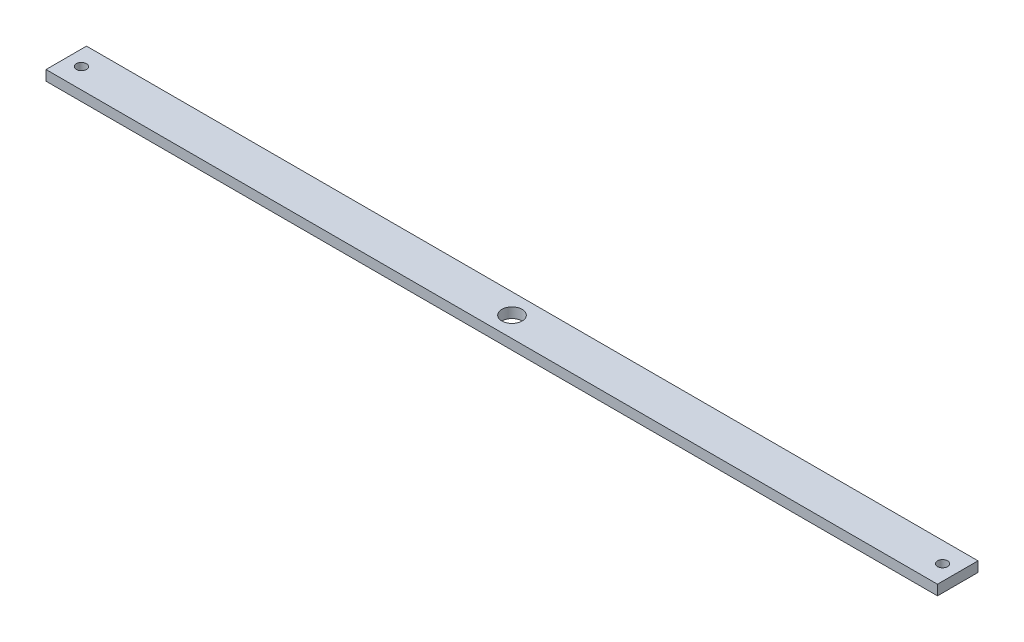
SolidWorks part; units mm, degrees
ref_plane "Front Plane" through (0, 0, 0) normal (0, 0, 1) x (1, 0, 0)
ref_plane "Top Plane" through (0, 0, 0) normal (0, 1, 0) x (1, 0, 0)
ref_plane "Right Plane" through (0, 0, 0) normal (1, 0, 0) x (0, 0, -1)
sketch "Sketch1" plane through (0, 0, 0) normal (0, 1, 0) x (1, 0, 0)
  line L1 (-279.4, -12.7) -> (279.4, -12.7)
  line L2 (-279.4, -12.7) -> (-279.4, 12.7)
  line L3 (-279.4, 12.7) -> (279.4, 12.7)
  line L4 (279.4, -12.7) -> (279.4, 12.7)
  line L5 (-279.4, -12.7) -> (279.4, 12.7) construction
  line L6 (-279.4, 12.7) -> (279.4, -12.7) construction
  point P0 (0, 0)
  dimension "D1" = 558.8
  dimension "D2" = 25.4
extrude "Boss-Extrude1" add sketch "Sketch1" along normal blind 6.35
hole_wizard "1/4 (0.25) Diameter Hole1" positions "Sketch3" profile "Sketch4" hole size "1/4" standard "ANSI Inch"
sketch "Sketch3" plane through (0, 6.35, 0) normal (0, 1, 0) x (1, 0, 0)
  line L0 (-279.4, 0) -> (-269.875, 0) construction
  line L1 (-279.4, 12.7) -> (-279.4, -12.7) construction
  line L4 (279.4, 0) -> (269.875, 0) construction
  line L5 (279.4, -12.7) -> (279.4, 12.7) construction
  point P2 (-269.875, 0)
  point P10 (269.875, 0)
  dimension "D1" = 9.525
sketch "Sketch4" plane through (-269.875, 6.35, 0) normal (1, 0, 0) x (0, 0, 1)
  line L0 (0, 0) -> (0, 18.9273)
  line L1 (0, 18.9273) -> (3.175, 17.0195)
  line L2 (3.175, 17.0195) -> (3.175, 0)
  line L5 (3.175, 0) -> (0, 0)
  line L10 (0, 18.9273) -> (-3.175, 17.0195) construction
  line L11 (0, -6.35) -> (0, 107.95) construction
  dimension "Hole Dia." = 6.35
  dimension "Hole Depth" = 17.0195
  dimension "Drill Angle" = 118
sketch "Sketch5" plane through (0, 6.35, 0) normal (0, 1, 0) x (1, 0, 0)
  circle A0 centre (0, 0) radius 6.35
  dimension "D1" = 12.7
extrude "Cut-Extrude1" cut sketch "Sketch5" against normal through all
